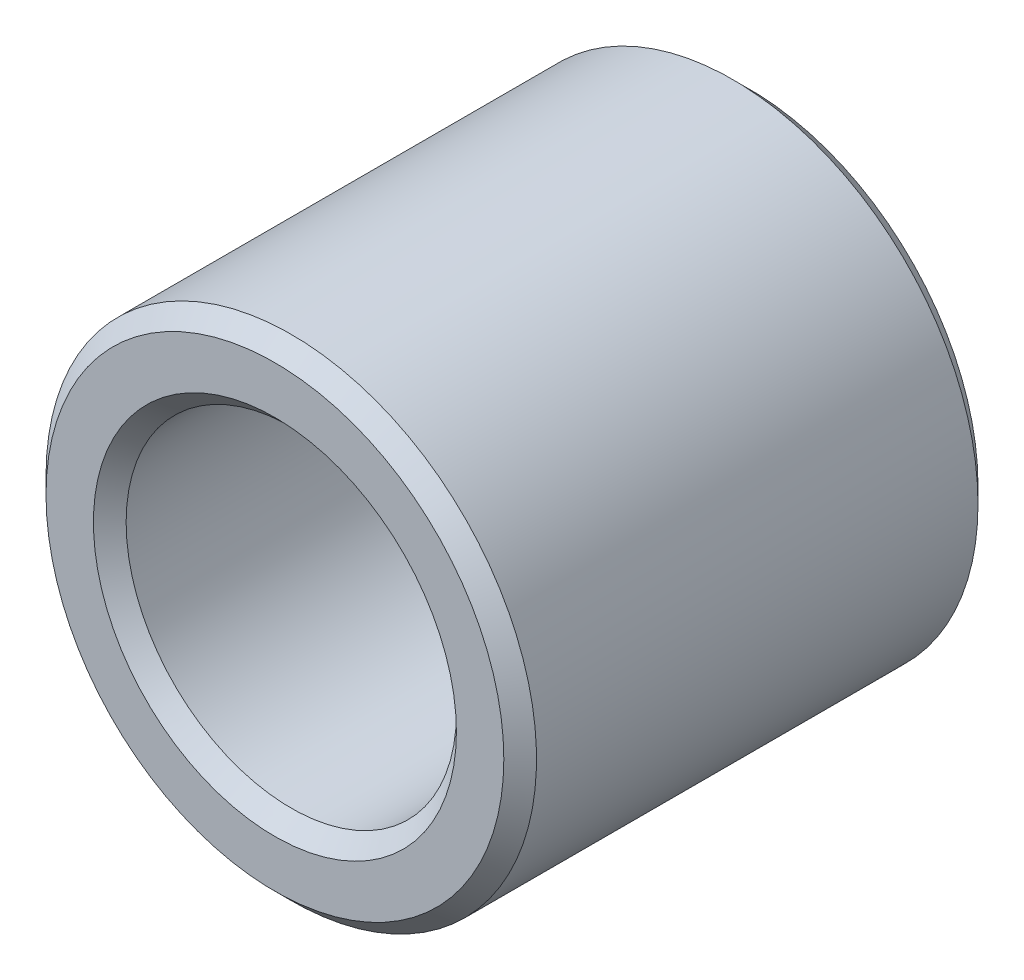
SolidWorks part; units mm, degrees
material "ASTM A36 Aço"
ref_plane "Plano frontal" through (0, 0, 0) normal (0, 0, 1) x (1, 0, 0)
ref_plane "Plano superior" through (0, 0, 0) normal (0, 1, 0) x (1, 0, 0)
ref_plane "Plano direito" through (0, 0, 0) normal (1, 0, 0) x (0, 0, -1)
sketch "Esboço1" plane through (0, 0, 0) normal (0, 0, 1) x (1, 0, 0)
  circle A0 centre (0, 0) radius 5.05
  circle A1 centre (0, 0) radius 7.5
  dimension "D1" = 10.1
  dimension "D2" = 15
extrude "Ressalto-extrusão1" add sketch "Esboço1" along normal mid plane 14.5
chamfer "Chanfro1" distance 0.5 angle 45 4 edges at (5.05, 0, -7.25) (7.5, 0, -7.25) (5.05, 0, 7.25) (7.5, 0, 7.25)
